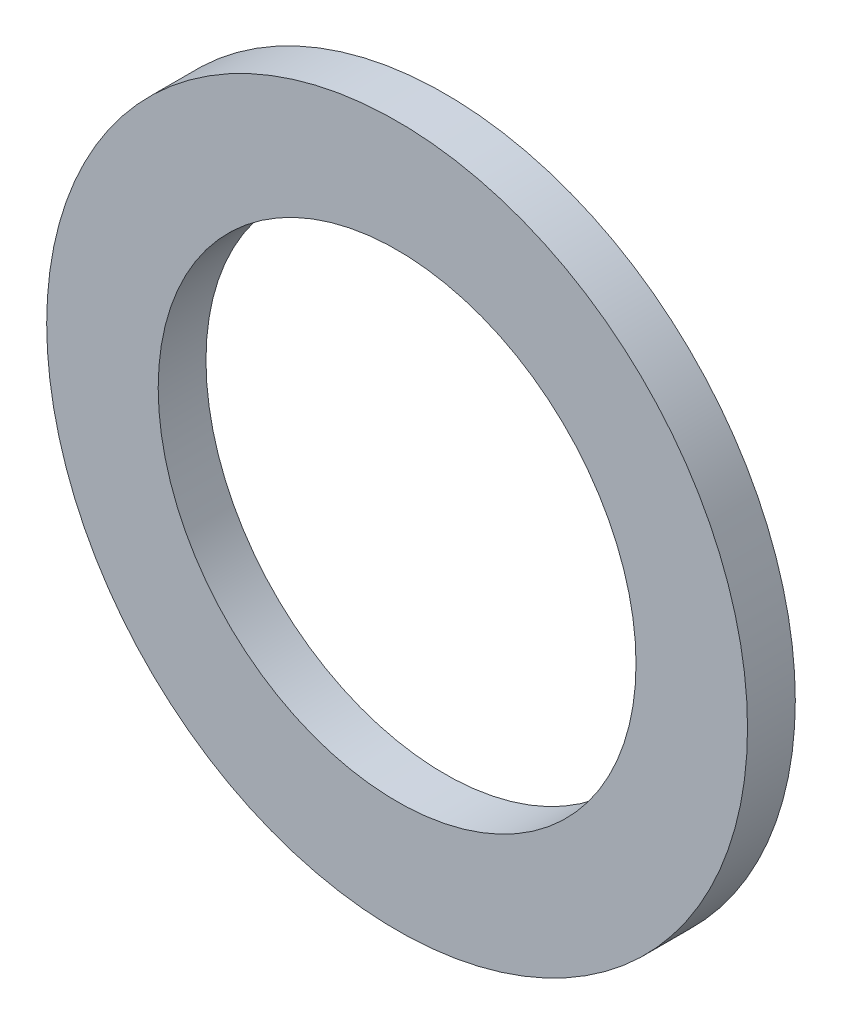
SolidWorks part; units mm, degrees
ref_plane "Спереди" through (0, 0, 0) normal (0, 0, 1) x (1, 0, 0)
ref_plane "Сверху" through (0, 0, 0) normal (0, 1, 0) x (1, 0, 0)
ref_plane "Справа" through (0, 0, 0) normal (1, 0, 0) x (0, 0, -1)
sketch "Эскиз1" plane through (0, 0, 0) normal (0, 0, 1) x (1, 0, 0)
  circle A0 centre (0, 0) radius 11
  dimension "D1" = 22
extrude "Вытянуть1" add sketch "Эскиз1" along normal blind 1.5
sketch "Эскиз2" plane through (0, 0, 1.5) normal (0, 0, 1) x (1, 0, 0)
  circle A0 centre (0, 0) radius 7.5
  dimension "D1" = 15
extrude "Вырез-Вытянуть1" cut sketch "Эскиз2" against normal blind 1.5
